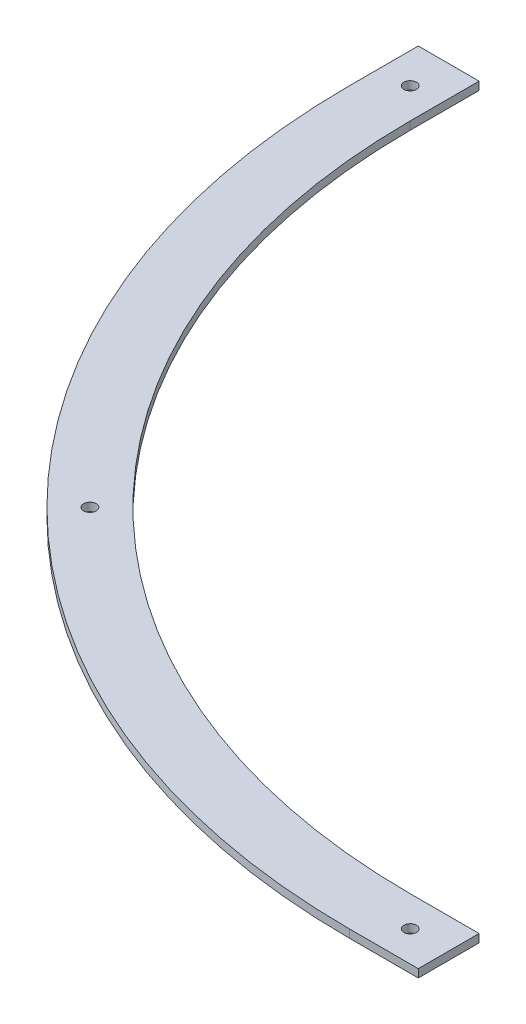
SolidWorks part; units mm, degrees
ref_plane "Front Plane" through (0, 0, 0) normal (0, 0, 1) x (1, 0, 0)
ref_plane "Top Plane" through (0, 0, 0) normal (0, 1, 0) x (1, 0, 0)
ref_plane "Right Plane" through (0, 0, 0) normal (1, 0, 0) x (0, 0, -1)
sketch "Sketch1" plane through (0, 0, 0) normal (0, 1, 0) x (1, 0, 0)
  line L0 (-82.5, 107) -> (-82.5, 90) construction
  line L1 (-90, -90) -> (90, -90) construction
  line L2 (-90, -90) -> (-90, 90) construction
  line L3 (-90, 90) -> (90, 90) construction
  line L4 (90, -90) -> (90, 90) construction
  line L5 (-90, -90) -> (90, 90) construction
  line L6 (-90, 90) -> (90, -90) construction
  line L8 (-90, 90) -> (-90, 107)
  line L9 (-90, 107) -> (-75, 107)
  line L10 (-75, 90) -> (-75, 107)
  line L11 (90, -75) -> (107, -75)
  line L13 (90, -90) -> (107, -90)
  line L14 (107, -75) -> (107, -90)
  line L15 (90, -82.5) -> (107, -82.5) construction
  arc A0 (-90, 90) -> (90, -90) centre (90, 90) ccw
  arc A1 (-75, 90) -> (90, -75) centre (90, 90) ccw
  arc A2 (-81.6603, 107) -> (107, -81.6603) centre (90, 90) ccw construction
  circle A3 centre (-82.5, 97.5) radius 1.55
  circle A4 centre (97.5, -82.5) radius 1.55
  circle A5 centre (-31.9759, -31.9759) radius 1.55
  point P0 (0, 0)
  dimension "D2" = 330
  dimension "D3" = 345
  dimension "D5" = 3.1
  dimension "D7" = 3.1
  dimension "D9" = 3.1
  dimension "D1" = 180
  dimension "D4" = 17
  dimension "D6" = 7.5
  dimension "D8" = 7.5
extrude "Boss-Extrude1" add sketch "Sketch1" along normal blind 2
